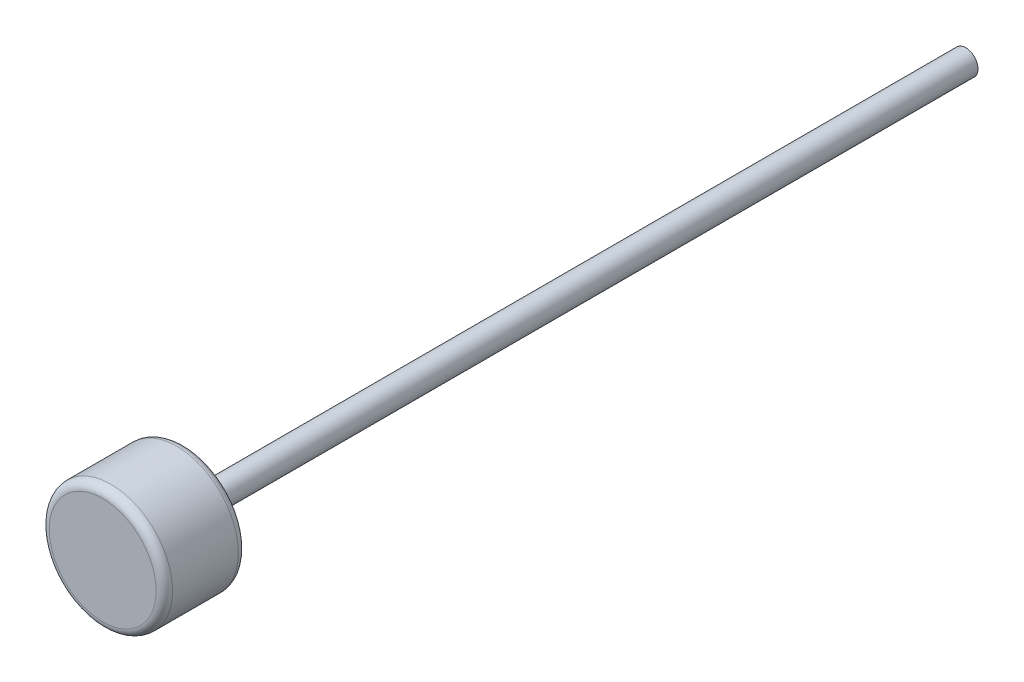
SolidWorks part; units mm, degrees
ref_plane "Front Plane" through (0, 0, 0) normal (0, 0, 1) x (1, 0, 0)
ref_plane "Top Plane" through (0, 0, 0) normal (0, 1, 0) x (1, 0, 0)
ref_plane "Right Plane" through (0, 0, 0) normal (1, 0, 0) x (0, 0, -1)
sketch "Sketch1" plane through (0, 0, 0) normal (0, 0, 1) x (1, 0, 0)
  circle A0 centre (0, 0) radius 1.5
  dimension "D1" = 3
extrude "Boss-Extrude1" add sketch "Sketch1" along normal blind 95
sketch "Sketch2" plane through (0, 0, 95) normal (0, 0, 1) x (1, 0, 0)
  circle A0 centre (0, 0) radius 7.5
  dimension "D1" = 15
extrude "Boss-Extrude2" add sketch "Sketch2" along normal blind 10
fillet "Fillet1" radius 1 1 edges at (7.5, 0, 105)
fillet "Fillet2" radius 1 1 edges at (7.5, 0, 95)
